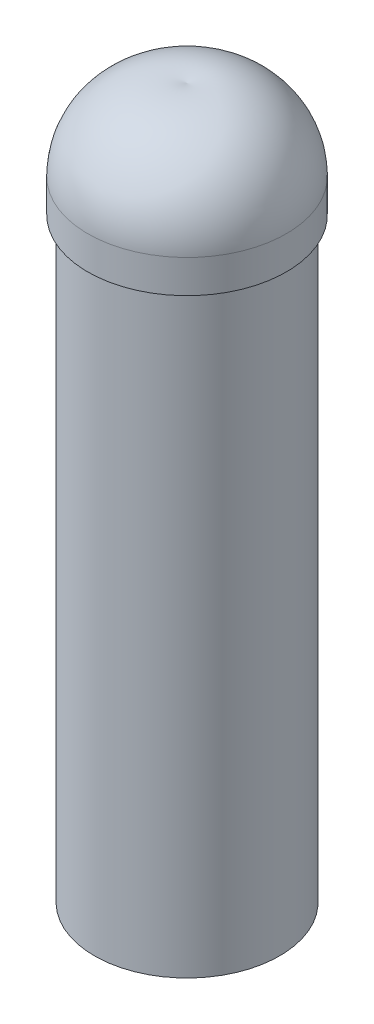
SolidWorks part; units mm, degrees
ref_plane "Přední rovina" through (0, 0, 0) normal (0, 0, 1) x (1, 0, 0)
ref_plane "Horní rovina" through (0, 0, 0) normal (0, 1, 0) x (1, 0, 0)
ref_plane "Pravá rovina" through (0, 0, 0) normal (1, 0, 0) x (0, 0, -1)
sketch "Sketch1" plane through (0, 0, 0) normal (0, 0, 1) x (1, 0, 0)
  line L0 (-2.75, 13.1121) -> (-2.75, -4.8879)
  line L1 (-2.75, -4.8879) -> (-1.55, -4.8879)
  line L2 (-1.55, -4.8879) -> (-1.55, 2.2623)
  line L3 (-1.55, 2.2623) -> (0.05, 2.2623)
  line L6 (-2.95, 14.1121) -> (-2.95, 13.1121)
  line L7 (-2.95, 13.1121) -> (-2.75, 13.1121)
  line L8 (0.05, 16.5616) -> (0.05, 2.2623)
  arc A0 (-2.95, 14.1121) -> (0.05, 16.5616) centre (-0.45, 14.1121) cw
  dimension "D2" = 2.5
  dimension "D1" = 18
  dimension "D3" = 1.6
  dimension "D4" = 1.2
  dimension "D5" = 1
  dimension "D6" = 3
revolve "Revolve1" add sketch "Sketch1" angle 360 about L8
